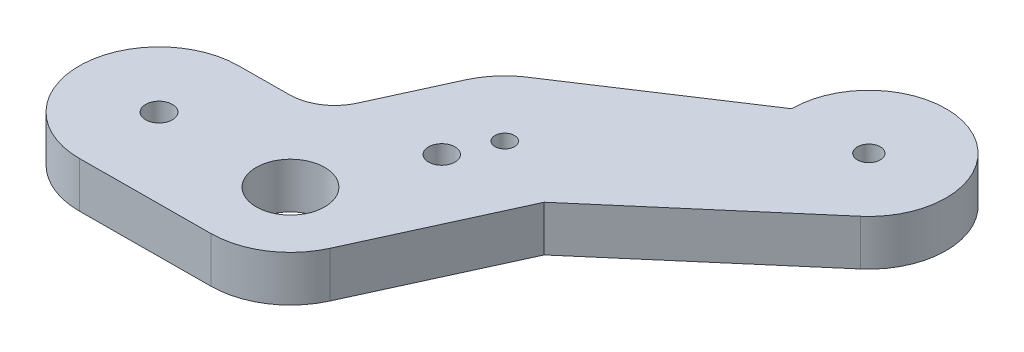
SolidWorks part; units mm, degrees
ref_plane "Front Plane" through (0, 0, 0) normal (0, 0, 1) x (1, 0, 0)
ref_plane "Top Plane" through (0, 0, 0) normal (0, 1, 0) x (1, 0, 0)
ref_plane "Right Plane" through (0, 0, 0) normal (1, 0, 0) x (0, 0, -1)
sketch "Sketch1" plane through (0, 0, 0) normal (0, 1, 0) x (1, 0, 0)
  line L0 (-5.7048, -3.5323) -> (0.0198, -3.4999)
  line L1 (-5.7444, 3.4676) -> (-3.5308, 3.4801)
  line L2 (-1.7232, 4.6485) -> (-0.2388, 7.8954)
  line L3 (6.1275, 4.9849) -> (3.1831, -1.4553)
  arc A0 (0.0198, -3.4999) -> (3.1831, -1.4553) centre (0, 0) ccw
  arc A1 (6.1275, 4.9849) -> (-0.2388, 7.8954) centre (2.9444, 6.4402) ccw
  arc A2 (-5.7444, 3.4676) -> (-5.7048, -3.5323) centre (-5.7246, -0.0324) ccw
  arc A3 (-1.7232, 4.6485) -> (-3.5308, 3.4801) centre (-3.5421, 5.4801) cw
  circle A4 centre (0, 0) radius 1.5
  circle A5 centre (-5.7246, -0.0324) radius 0.5861
  circle A6 centre (2.9444, 6.4402) radius 0.4259
  point P6 (2.9444, 6.4402)
  dimension "D1" = 7
  dimension "D2" = 2
  dimension "D3" = 3
extrude "Boss-Extrude1" add sketch "Sketch1" along normal blind 2
sketch "Sketch3" plane through (0, 2, 0) normal (0, 1, 0) x (1, 0, 0)
  circle A0 centre (2.0737, 4.5514) radius 0.5796
extrude "Cut-Extrude1" cut sketch "Sketch3" against normal up to surface (2 mm away) up to face at (-1.1484, 0, -2.3033)
sketch "Sketch4" plane through (0, 2, 0) normal (0, 1, 0) x (1, 0, 0)
  line L1 (13.5834, 11.3761) -> (6.1275, 4.9849)
  line L3 (7.9971, 13.9453) -> (0.874, 9.2622)
  line L4 (0.874, 9.2622) -> (6.1275, 4.9849)
  arc A0 (13.5834, 11.3761) -> (7.9971, 13.9453) centre (11.3811, 13.9453) ccw
  circle A1 centre (11.3811, 13.9453) radius 0.5
  arc A2 (6.1275, 4.9849) -> (-0.2388, 7.8954) centre (2.9444, 6.4402) ccw construction
  point P2 (6.1275, 4.9849)
  point P3 (-0.2388, 7.8954)
  point P7 (0, 7.8954)
  point P8 (0.874, 9.2622)
  dimension "D1" = 1
  dimension "D2" = 18
extrude "Boss-Extrude3" add sketch "Sketch4" against normal up to surface (2 mm away) up to face at (2.0737, 0, -3.9718)
